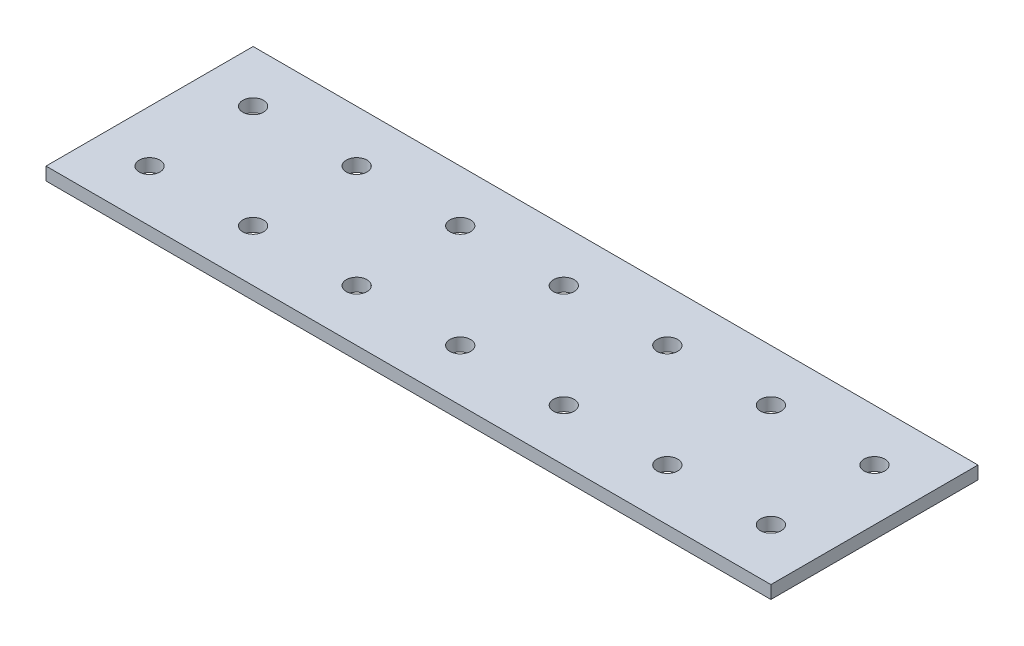
SolidWorks part; units mm, degrees
ref_plane "Front Plane" through (0, 0, 0) normal (0, 0, 1) x (1, 0, 0)
ref_plane "Top Plane" through (0, 0, 0) normal (0, 1, 0) x (1, 0, 0)
ref_plane "Right Plane" through (0, 0, 0) normal (1, 0, 0) x (0, 0, -1)
sketch "Sketch2" plane through (0, 0, 0) normal (0, 1, 0) x (1, 0, 0)
  line L1 (-88.9, -25.4) -> (88.9, -25.4)
  line L2 (-88.9, -25.4) -> (-88.9, 25.4)
  line L3 (-88.9, 25.4) -> (88.9, 25.4)
  line L4 (88.9, -25.4) -> (88.9, 25.4)
  line L5 (-88.9, -25.4) -> (88.9, 25.4) construction
  line L6 (-88.9, 25.4) -> (88.9, -25.4) construction
  circle A0 centre (-76.2, -12.7) radius 2.54
  circle A1 centre (-76.2, 12.7) radius 2.54
  circle A3 centre (-50.8, -12.7) radius 2.54
  circle A4 centre (-50.8, 12.7) radius 2.54
  circle A5 centre (-25.4, -12.7) radius 2.54
  circle A6 centre (-25.4, 12.7) radius 2.54
  circle A7 centre (0, -12.7) radius 2.54
  circle A8 centre (0, 12.7) radius 2.54
  circle A9 centre (25.4, -12.7) radius 2.54
  circle A10 centre (25.4, 12.7) radius 2.54
  circle A11 centre (50.8, -12.7) radius 2.54
  circle A12 centre (50.8, 12.7) radius 2.54
  circle A13 centre (76.2, -12.7) radius 2.54
  circle A14 centre (76.2, 12.7) radius 2.54
  point P0 (0, 0)
  dimension "D2" = 5.08
  dimension "D4" = 12.7
  dimension "D7" = 12.7
  dimension "D1" = 50.8
  dimension "D6" = 177.8
  dimension "D3" = 2
  dimension "D5" = 7
extrude "Boss-Extrude1" add sketch "Sketch2" along normal blind 3.175
